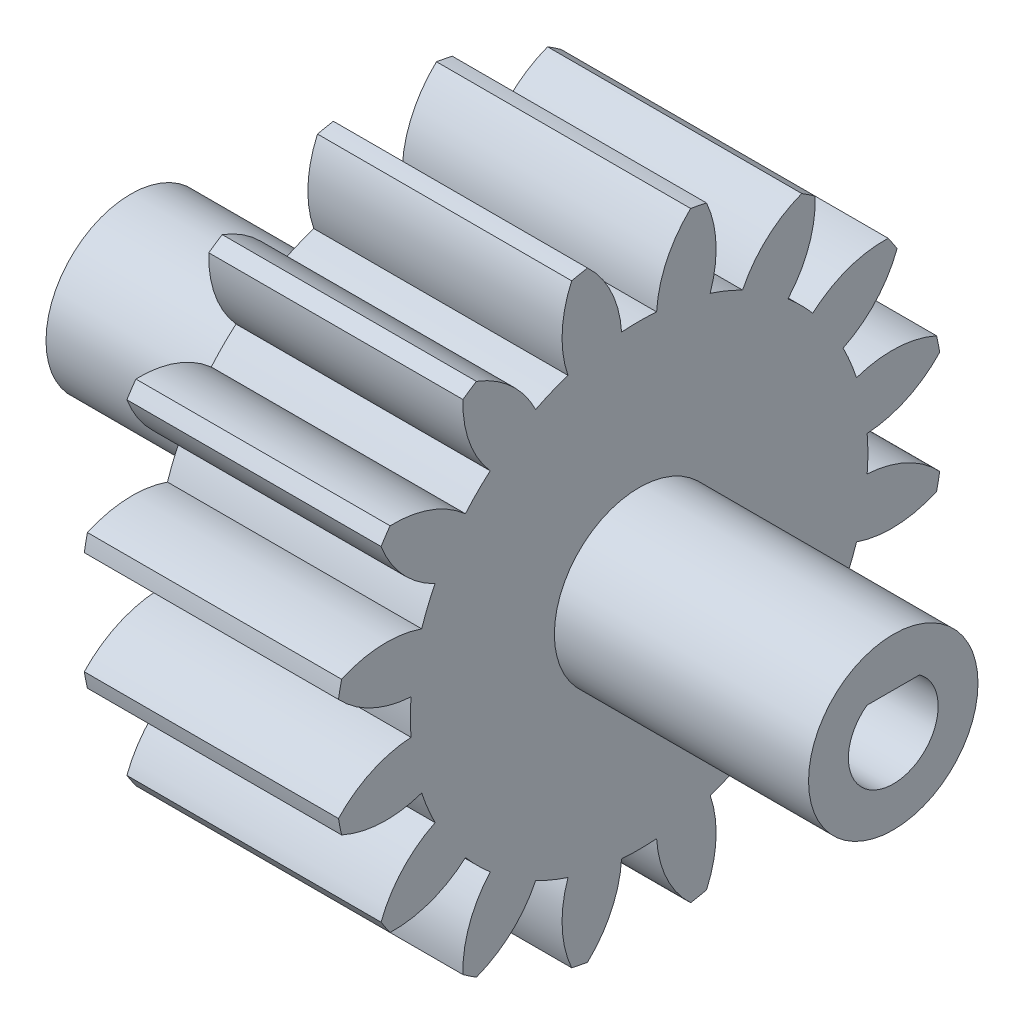
SolidWorks part; units mm, degrees
ref_plane "Plane1" through (0, 0, 0) normal (0, 0, 1) x (1, 0, 0)
ref_plane "Plane2" through (0, 0, 0) normal (0, 1, 0) x (1, 0, 0)
ref_plane "Plane3" through (0, 0, 0) normal (1, 0, 0) x (0, 0, -1)
other "Configuration Table"
sketch "HoldingSke" plane through (0, 0, 0) normal (0, 1, 0) x (1, 0, 0)
  line L0 (0, 0) -> (0.4806, -0.1378)
  line L1 (-15, 0) -> (100, 0) construction
  line L2 (0, 0) -> (-2.1039, 2.3779)
  line L3 (0, 0) -> (-11.863, 4.5341)
  line L4 (0, 0) -> (8.3015, 2.3804)
  line L5 (0, 0) -> (-42.1629, -15.7255)
  line L6 (0, 0) -> (-12.4344, -8.3896)
  line L7 (-2.1039, 2.3779) -> (7.5823, 46.3231)
  line L8 (-76.2, 54.61) -> (-75.3, 54.61)
  line L9 (-71.009, 38.7566) -> (-53.1078, 45.2721)
  line L10 (-76.2, 71.12) -> (104.1128, 71.12)
  line L11 (0, 0) -> (-15, 0)
  line L12 (-76.2, 101.6) -> (-76.133, 101.6)
  line L13 (24.9733, 27.94) -> (52.9518, 28.4284)
  line L14 (24.9733, 27.94) -> (24.9743, 27.94)
  line L15 (24.9733, 27.94) -> (100.4006, 29.5858)
  line L16 (-63.627, -2) -> (-12.827, -2)
  circle A0 centre (0, 0) radius 2.5
  circle A1 centre (0, 0) radius 5
  circle A2 centre (0, 0) radius 5
  circle A3 centre (0, 0) radius 2.5
  dimension "MHD" = 10
  dimension "Hub_dia" = 10
  dimension "Bore" = 5
  dimension "MBD" = 5
  dimension "Num_teeth" = 16
  dimension "Pitch" = 0.5
  dimension "Overall_len" = 45
  dimension "Show_teeth" = 16
  dimension "Thickness" = 15
  dimension "OAL" = 45.0001
  dimension "T_dim" = 0.9
  dimension "Ap" = 20
  dimension "H" = 19.05
  dimension "Pitch_radius" = 180.3128
  dimension "Width" = 15
  dimension "Backlash" = 0.067
  dimension "Addendum_fac" = 1
  dimension "Dedendum_fac" = 1.25
  dimension "Clearance_fac" = 0.25
  dimension "Dedendum_add" = 0.001
  dimension "Module" = 2
sketch "BasProSke" plane through (0, 0, 0) normal (0, 1, 0) x (1, 0, 0)
  line L0 (-10, 0) -> (60, 0) construction
  line L1 (0, 0) -> (0, 18)
  line L2 (0, 0) -> (15, 0)
  line L3 (15, 0) -> (15, 18)
  line L4 (15, 18) -> (0, 18)
  dimension "Thickness" = 15
  dimension "Diameter" = 36
revolve "Base-Revolve" add sketch "BasProSke" angle 360 about L0
sketch "TooCutSke" plane through (0, 0, 0) normal (1, 0, 0) x (0, 0, -1)
  line L1 (0, 0) -> (0, 107) construction
  line L2 (0, 0) -> (-1.6854, 15.911) construction
  line L3 (0, 0) -> (-6.2172, 31.2558) construction
  line L4 (-1.6854, 15.911) -> (-3.1086, 15.6279) construction
  arc A0 (1.0343, 13.4593) -> (-1.0343, 13.4593) centre (0, 0) ccw
  arc A1 (3.0657, 17.7628) -> (-3.0657, 17.7628) centre (0, 0) ccw
  circle A2 centre (0, 0) radius 16 construction
  circle A3 centre (0, 0) radius 15.0351 construction
  arc A4 (-1.0343, 13.4593) -> (-3.0657, 17.7628) centre (-7.4228, 13.075) ccw
  arc A5 (3.0657, 17.7628) -> (1.0343, 13.4593) centre (7.4228, 13.075) ccw
  dimension "Root_dia" = 26.998
  dimension "Overcut_dia" = 36.0508
  dimension "Pitch_dia" = 32
  dimension "Base_dia" = 30.0702
  dimension "Flank_rad" = 6.4
  dimension "Half_ang" = 11.25
  dimension "Half_CT" = 1.451
extrude "ToothCut" cut sketch "TooCutSke" along normal through all
fillet "Breaks" [suppressed] radius 0.04
fillet "RootFillets" [suppressed] radius 0.501
pattern_circular "TeethCuts" count 16 every 22.5 about axis through (-10, 0, 0) along (1, 0, 0) of "ToothCut", "RootFillets", "Breaks"
sketch "HubNeaOneSke" plane through (0, 0, 0) normal (-1, 0, 0) x (0, 0, 1)
  circle A0 centre (0, 0) radius 5
  dimension "Diameter" = 10
extrude "HubNearOne" [suppressed] add sketch "HubNeaOneSke" along normal blind 30.0001
sketch "HubNeaBotSke" plane through (0, 0, 0) normal (-1, 0, 0) x (0, 0, 1)
  circle A0 centre (0, 0) radius 5
  dimension "Diameter" = 10
extrude "HubNearBoth" add sketch "HubNeaBotSke" along normal blind 15
ref_plane "FarPln" through (15, 0, 0) normal (1, 0, 0) x (0, 0, -1)
sketch "HubFarSke" plane through (15, 0, 0) normal (1, 0, 0) x (0, 0, -1)
  circle A0 centre (0, 0) radius 5
  dimension "Diameter" = 10
extrude "HubFar" add sketch "HubFarSke" along normal blind 15
sketch "BorSke" plane through (0, 0, 0) normal (1, 0, 0) x (0, 0, -1)
  circle A0 centre (0, 0) radius 2.5
  dimension "Diameter" = 5
extrude "Bore" cut sketch "BorSke" along normal mid plane 90.0001
sketch "KeySke" plane through (0, 0, 0) normal (1, 0, 0) x (0, 0, -1)
  line L0 (-1, 0) -> (-1, 3.4)
  line L1 (-1, 3.4) -> (1, 3.4)
  line L2 (1, 3.4) -> (1, 0)
  line L3 (0, 0) -> (0, 34) construction
  line L4 (-1, 0) -> (1, 0)
  dimension "Offset" = 3.4
  dimension "Width" = 2
extrude "Keyway" [suppressed] cut sketch "KeySke" along normal mid plane 90.0001
pattern_circular "Keyway2" [suppressed] count 2 every 90 about axis through (-10, 0, 0) along (1, 0, 0)
sketch "Sketch1" plane through (30, 0, 0) normal (1, 0, 0) x (0, 0, -1)
  line L0 (-1.5, 2) -> (1.5, 2)
  circle A0 centre (0, 0) radius 2.5 construction
  arc A3 (1.5, 2) -> (-1.5, 2) centre (0, 0) ccw
  dimension "D2" = 2
extrude "Boss-Extrude1" add sketch "Sketch1" against normal up to surface (45.0001 mm away) up to face at (-15, 0, 2.5)
sketch "Sketch2" plane through (30, 0, 0) normal (1, 0, 0) x (0, 0, -1)
  line L0 (-1.5, 2) -> (1.5, 2) construction
  line L1 (-1.5, 2) -> (1.5, 2)
  line L2 (-1.5492, 2.15) -> (1.5492, 2.15)
  arc A0 (-1.5, 2) -> (1.5, 2) centre (0, 0) ccw construction
  arc A1 (-1.5, 2) -> (1.5, 2) centre (0, 0) ccw
  arc A3 (-1.5492, 2.15) -> (1.5492, 2.15) centre (0, 0) ccw
  dimension "D1" = 0.15
extrude "Cut-Extrude1" cut sketch "Sketch2" against normal through all
equation "' \"Module@HoldingSke\" = 6.35"
equation "' \"Num_teeth@HoldingSke\" = 12"
equation "' \"Ap@HoldingSke\" =  20"
equation "' \"Ap@HoldingSke\" = 20"
equation "' \"Width@HoldingSke\" = 0.5 * 25.4"
equation "' \"Hub_dia@HoldingSke\"= 1 * 25.4"
equation "' \"Hub_dia@HoldingSke\" = 1 * 25.4"
equation "' \"Overall_len@HoldingSke\" = 1.0 * 25.4"
equation "' \"Bore@HoldingSke\" = 0.75 * 25.4"
equation "' \"T_dim@HoldingSke\" = 0.1 * 25.4"
equation "' \"Width@KeySke\" = 0.25 * 25.4"
equation "' \"Show_teeth@HoldingSke\" = 13"
equation "' \"Backlash@HoldingSke\" = 0.009 * 25.4"
equation "' \"Addendum_fac@HoldingSke\" = 1.0"
equation "' \"Dedendum_fac@HoldingSke\" = 1.25"
equation "' \"Dedendum_add@HoldingSke\" = 0.00005 * 25.4"
equation "' \"Clearance_fac@HoldingSke\" = 0.25"
equation "\"Pitch@HoldingSke\" = 1 / \"Module@HoldingSke\""
equation "\"Overcut_dia@TooCutSke\" = (\"Num_teeth@HoldingSke\" + 2 * \"Addendum_fac@HoldingSke\") / \"Pitch@HoldingSke\" + 0.002 * 25.4"
equation "\"Pitch_dia@TooCutSke\" = \"Num_teeth@HoldingSke\" / \"Pitch@HoldingSke\""
equation "\"Base_dia@TooCutSke\" = \"Num_teeth@HoldingSke\" / \"Pitch@HoldingSke\" * cos((\"Ap@HoldingSke\"  * 3.14159265 / 180))"
equation "\"Root_dia@TooCutSke\" = (\"Num_teeth@HoldingSke\" + 2) / \"Pitch@HoldingSke\" - 2 * (\"Addendum_fac@HoldingSke\" + \"Dedendum_fac@HoldingSke\") / \"Pitch@HoldingSke\" - \"Dedendum_add@HoldingSke\" * 2"
equation "\"Half_ang@TooCutSke\" = 180 / \"Num_teeth@HoldingSke\""
equation "\"Half_CT@TooCutSke\" = \"Num_teeth@HoldingSke\" / \"Pitch@HoldingSke\" * sin((3.14159265 / 2 / \"Num_teeth@HoldingSke\")) / 2 - 7 * \"Backlash@HoldingSke\" / 4"
equation "\"Flank_rad@TooCutSke\" = \"Num_teeth@HoldingSke\" / \"Pitch@HoldingSke\" / 5"
equation "\"Radius@RootFillets\" = \"Clearance_fac@HoldingSke\" / \"Pitch@HoldingSke\" + \"Dedendum_add@HoldingSke\""
equation "\"Break_rad@Breaks\" = 0.02 / \"Pitch@HoldingSke\""
equation "\"Thickness@HoldingSke\" = \"Width@HoldingSke\""
equation "\"OAL@HoldingSke\" = \"Thickness@HoldingSke\""
equation "\"MHD@HoldingSke\" = (\"Num_teeth@HoldingSke\" + 2) / \"Pitch@HoldingSke\" - 2 * (\"Addendum_fac@HoldingSke\" + \"Dedendum_fac@HoldingSke\")  / \"Pitch@HoldingSke\" - \"Dedendum_add@HoldingSke\" * 2"
equation "\"MBD@HoldingSke\" = (\"Num_teeth@HoldingSke\" + 2) / \"Pitch@HoldingSke\" - 2 * (\"Addendum_fac@HoldingSke\" + \"Dedendum_fac@HoldingSke\")  / \"Pitch@HoldingSke\" - \"Dedendum_add@HoldingSke\" * 2 - 0.002 * 25.4"
equation "\"MHD@HoldingSke\" = ((sgn( \"MHD@HoldingSke\" - \"Hub_dia@HoldingSke\" )-1)*( \"MHD@HoldingSke\" - \"Hub_dia@HoldingSke\" ))/-2+ \"Hub_dia@HoldingSke\""
equation "\"MBD@HoldingSke\" = ((sgn( \"MBD@HoldingSke\" - \"Bore@HoldingSke\" )-1)*( \"MBD@HoldingSke\" - \"Bore@HoldingSke\" ))/-2+ \"Bore@HoldingSke\""
equation "\"OAL@HoldingSke\" = ((sgn( \"OAL@HoldingSke\" - \"Overall_len@HoldingSke\" )+1)*( \"OAL@HoldingSke\" - \"Overall_len@HoldingSke\" ))/2 + \"Overall_len@HoldingSke\" + 0.000002 * 25.4"
equation "\"Num_teeth@TeethCuts\" = int( \"Show_teeth@HoldingSke\" ) + 1"
equation "\"Num_teeth@TeethCuts\" = ((sgn( \"Num_teeth@TeethCuts\" - \"Num_teeth@HoldingSke\" )-1)*( \"Num_teeth@TeethCuts\" - \"Num_teeth@HoldingSke\" ))/-2+ \"Num_teeth@HoldingSke\""
equation "\"Num_teeth@TeethCuts\" = ((sgn( \"Num_teeth@TeethCuts\" - 2.0)+1)*( \"Num_teeth@TeethCuts\" - 2.0))/2 +2.0"
equation "\"Angle@TeethCuts\" = 360.0 / \"Num_teeth@HoldingSke\""
equation "\"Diameter@BasProSke\" = (\"Num_teeth@HoldingSke\" + 2 * \"Addendum_fac@HoldingSke\") / \"Pitch@HoldingSke\""
equation "\"Thickness@BasProSke\"  = \"Thickness@HoldingSke\""
equation "' \"Fillet_rad@BasProSke\" =  \"Thickness@HoldingSke\" * 0.05"
equation "' \"Fillet_rad@BasProSke\" = \"Thickness@HoldingSke\" * 0.05"
equation "\"MHD@HoldingSke\" = ((sgn( \"MHD@HoldingSke\" - \"Root_dia@TooCutSke\" )-1)*( \"MHD@HoldingSke\" - \"Root_dia@TooCutSke\" ))/-2+ \"Root_dia@TooCutSke\""
equation "\"Diameter@HubNeaOneSke\" = \"MHD@HoldingSke\""
equation "\"Length@HubNearOne\" = \"OAL@HoldingSke\" - \"Thickness@BasProSke\""
equation "\"Diameter@HubNeaBotSke\" = \"MHD@HoldingSke\""
equation "\"Length@HubNearBoth\" = ( \"OAL@HoldingSke\" - \"Thickness@BasProSke\" ) / 2.0"
equation "\"Thickness@FarPln\" = \"Thickness@BasProSke\""
equation "\"Diameter@HubFarSke\" = \"MHD@HoldingSke\""
equation "\"Length@HubFar\" = ( \"OAL@HoldingSke\" - \"Thickness@BasProSke\" ) / 2.0"
equation "\"Diameter@BorSke\" = \"MBD@HoldingSke\""
equation "\"D1@Bore\" = \"OAL@HoldingSke\" * 2.0"
equation "\"D1@Keyway\" = \"OAL@HoldingSke\" * 2.0"
equation "\"Offset@KeySke\" = \"T_dim@HoldingSke\" + \"MBD@HoldingSke\" / 2.0"
